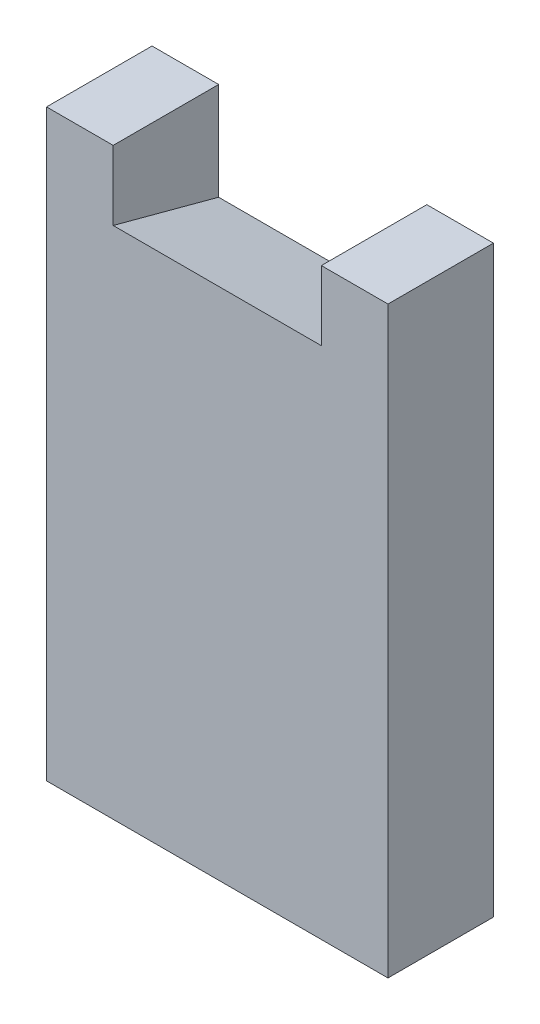
SolidWorks part; units mm, degrees
ref_plane "前视基准面" through (0, 0, 0) normal (0, 0, 1) x (1, 0, 0)
ref_plane "上视基准面" through (0, 0, 0) normal (0, 1, 0) x (1, 0, 0)
ref_plane "右视基准面" through (0, 0, 0) normal (1, 0, 0) x (0, 0, -1)
sketch "草图1" plane through (0, 0, 0) normal (0, 0, 1) x (1, 0, 0)
  line L1 (0, 0) -> (24.6, 0)
  line L2 (0, 0) -> (0, -42.055)
  line L3 (0, -42.055) -> (24.6, -42.055)
  line L4 (24.6, 0) -> (24.6, -42.055)
  line L5 (4.8, 0) -> (19.8, 0)
  line L6 (4.8, 0) -> (4.8, -5)
  line L7 (4.8, -5) -> (19.8, -5)
  line L8 (19.8, 0) -> (19.8, -5)
  point P9 (12.3, 0)
  dimension "D1" = 5
  dimension "D2" = 24.6
  dimension "D3" = 15
  dimension "D4" = 37.055
extrude "凸台-拉伸1" add sketch "草图1" along normal blind 7.6 contours L1 L8 L7 L6 L2 L3 L4
draft "拔模5" type of draft neutral plane draft angle 15 faces to draft 1 face at (12.3, -5, 3.8) neutral plane through (0, 0, 7.6) neutral plane normal (0, 0, 1) reverse direction yes parameters "D1"=15
